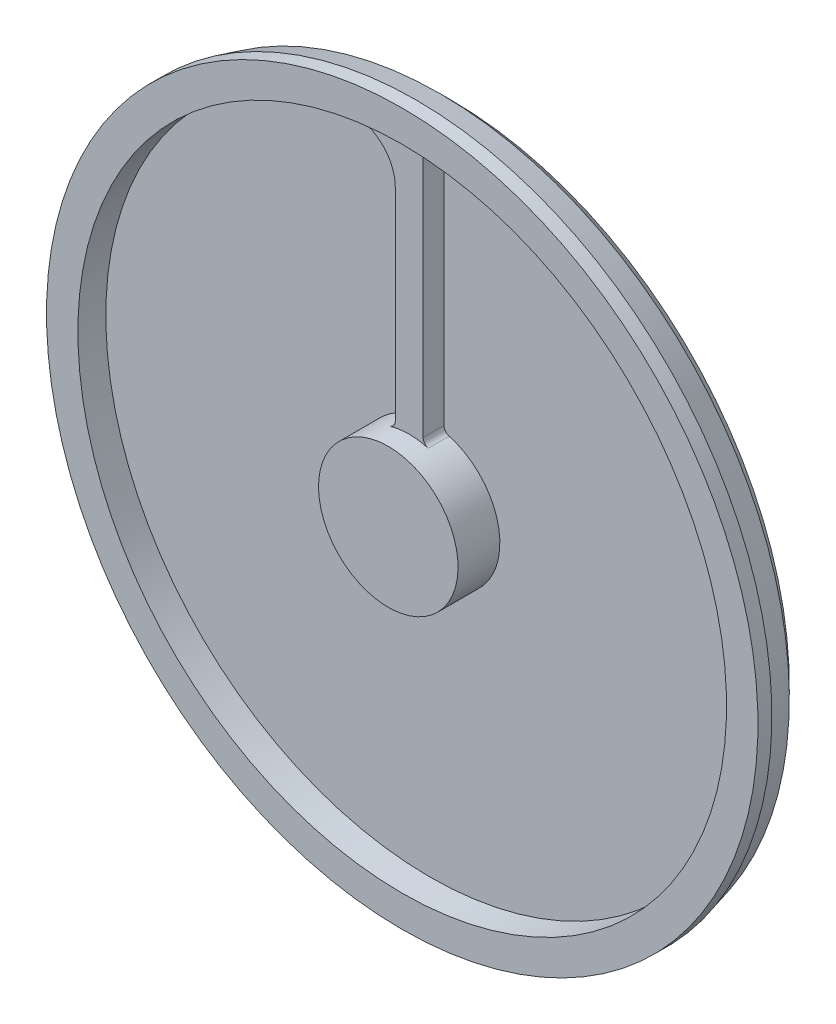
SolidWorks part; units mm, degrees
material "1060 Alloy"
ref_plane "Front Plane" through (0, 0, 0) normal (0, 0, 1) x (1, 0, 0)
ref_plane "Top Plane" through (0, 0, 0) normal (0, 1, 0) x (1, 0, 0)
ref_plane "Right Plane" through (0, 0, 0) normal (1, 0, 0) x (0, 0, -1)
sketch "Sketch1" plane through (0, 0, 0) normal (1, 0, 0) x (0, 0, -1)
  line L0 (0, 0) -> (0, 249.5455) construction
  line L1 (0, 0) -> (0, 485)
  line L2 (0, 0) -> (-30, 0)
  line L3 (-30, 100) -> (-30, 465)
  line L4 (-30, 465) -> (-70, 465)
  line L5 (-70, 465) -> (-70, 510)
  line L6 (-70, 510) -> (-50, 510)
  line L7 (-50, 510) -> (-15.8494, 500.8494)
  line L8 (-30, 0) -> (-90, 0)
  line L9 (-15.8494, 500.8494) -> (0, 485)
  line L10 (-30, 100) -> (-90, 100)
  line L11 (-90, 0) -> (-90, 100)
  line L12 (0, 0) -> (-186.6541, 0) construction
  dimension "D1" = 45
  dimension "D2" = 20
  dimension "D3" = 30
  dimension "D4" = 90
  dimension "D5" = 200
  dimension "D6" = 70
  dimension "D7" = 970
  dimension "D8" = 15
  dimension "D9" = 45
  dimension "D10" = 1020
revolve "Revolve1" add sketch "Sketch1" angle 360 about L12
sketch "Sketch2" plane through (0, 0, 30) normal (0, 0, 1) x (1, 0, 0)
  line L0 (-20, 464.5697) -> (-20, 97.9796)
  line L1 (20, 464.5697) -> (20, 97.9796)
  line L2 (0, 0) -> (0, 640.2584) construction
  circle A0 centre (0, 0) radius 465 construction
  circle A1 centre (0, 0) radius 100 construction
  arc A2 (20, 464.5697) -> (-20, 464.5697) centre (0, 0) ccw
  arc A3 (20, 97.9796) -> (-20, 97.9796) centre (0, 0) ccw
  dimension "D1" = 40
extrude "Boss-Extrude1" add sketch "Sketch2" along normal blind 30
fillet "Fillet1" radius 60 1 edges at (-20, 464.5697, 45)
fillet "Fillet2" radius 10 3 edges at (-20, 97.9796, 45) (20, 97.9796, 45) (20, 464.5697, 45)
pattern_circular "CirPattern1" [suppressed] count 9 over 360
